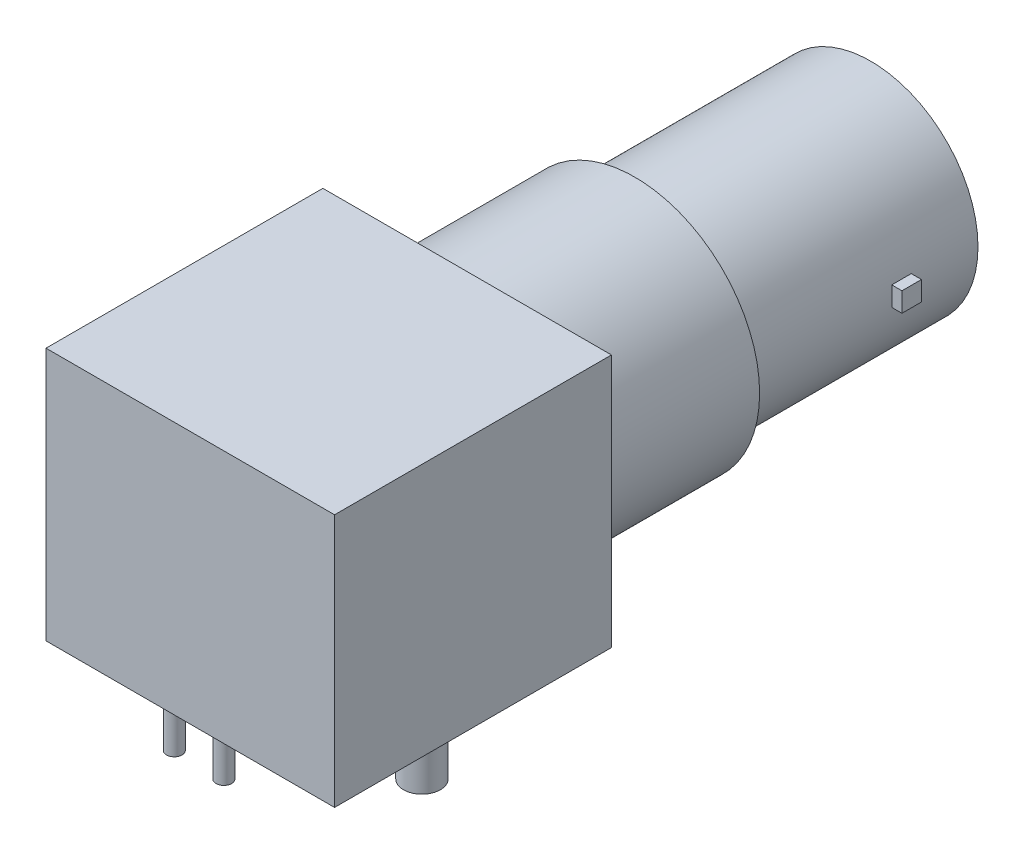
SolidWorks part; units mm, degrees
ref_plane "Спереди" through (0, 0, 0) normal (0, 0, 1) x (1, 0, 0)
ref_plane "Сверху" through (0, 0, 0) normal (0, 1, 0) x (1, 0, 0)
ref_plane "Справа" through (0, 0, 0) normal (1, 0, 0) x (0, 0, -1)
sketch "Эскиз1" plane through (0, 0, 0) normal (0, 0, 1) x (1, 0, 0)
  line L1 (-7.4, 6.5) -> (7.4, 6.5)
  line L2 (-7.4, 6.5) -> (-7.4, -6.5)
  line L3 (-7.4, -6.5) -> (7.4, -6.5)
  line L4 (7.4, 6.5) -> (7.4, -6.5)
  line L5 (-7.4, 6.5) -> (7.4, -6.5) construction
  line L6 (-7.4, -6.5) -> (7.4, 6.5) construction
  point P0 (0, 0)
extrude "Бобышка-Вытянуть1" add sketch "Эскиз1" against normal blind 14.2
sketch "Эскиз2" plane through (0, 0, -14.2) normal (0, 0, -1) x (-1, 0, 0)
  circle A0 centre (0, 0) radius 6.4
extrude "Бобышка-Вытянуть2" add sketch "Эскиз2" along normal blind 8.6
cosmetic thread "Условное изображение резьбы1" parameters "D2"=11.8
sketch "Эскиз3" plane through (0, 0, -22.8) normal (0, 0, -1) x (-1, 0, 0)
  circle A0 centre (0, 0) radius 5.5
  circle A1 centre (0, 0) radius 5
extrude "Бобышка-Вытянуть3" add sketch "Эскиз3" along normal blind 12.1
sketch "Эскиз4" plane through (0, 0, 0) normal (1, 0, 0) x (0, 0, -1)
  line L1 (30.5, 0.5) -> (31.5, 0.5)
  line L2 (30.5, 0.5) -> (30.5, -0.5)
  line L3 (30.5, -0.5) -> (31.5, -0.5)
  line L4 (31.5, 0.5) -> (31.5, -0.5)
  line L5 (30.5, 0.5) -> (31.5, -0.5) construction
  line L6 (30.5, -0.5) -> (31.5, 0.5) construction
  point P0 (31, 0)
extrude "Бобышка-Вытянуть4" add sketch "Эскиз4" along normal blind 6 and the other way blind 6
sketch "Эскиз7" plane through (0, -6.5, 0) normal (0, -1, 0) x (1, 0, 0)
  line L0 (-5.08, -6.8) -> (5.08, -6.8) construction
  line L2 (0, -1.72) -> (-2.54, -1.72) construction
  line L3 (-7.4, -14.2) -> (7.4, -14.2) construction
  circle A0 centre (5.08, -6.8) radius 0.95
  circle A1 centre (-5.08, -6.8) radius 0.95
  circle A2 centre (0, -1.72) radius 0.4
  circle A3 centre (-2.54, -1.72) radius 0.4
  point P13 (-6.412, -14.2)
  dimension "D1" = 5.08
  dimension "D4" = 5.08
  dimension "D2" = 10.16
  dimension "D3" = 7.4
  dimension "D5" = 0
  dimension "D6" = 2.54
extrude "Бобышка-Вытянуть5" add sketch "Эскиз7" along normal blind 3.3
sketch "Эскиз9" plane through (0, 0, 0) normal (0, 1, 0) x (1, 0, 0)
  line L0 (0, 43.297) -> (0, -10.9659) construction
